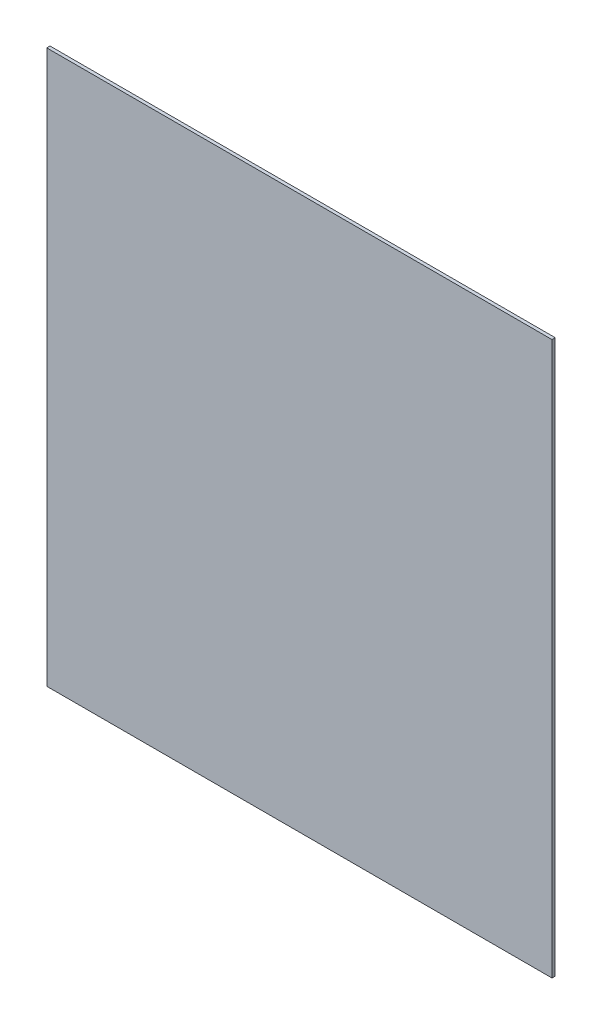
SolidWorks part; units mm, degrees
ref_plane "Přední rovina" through (0, 0, 0) normal (0, 0, 1) x (1, 0, 0)
ref_plane "Horní rovina" through (0, 0, 0) normal (0, 1, 0) x (1, 0, 0)
ref_plane "Pravá rovina" through (0, 0, 0) normal (1, 0, 0) x (0, 0, -1)
sketch "Skica1" plane through (0, 0, 0) normal (0, 0, 1) x (1, 0, 0)
  line L1 (-233, 255) -> (233, 255)
  line L2 (-233, 255) -> (-233, -255)
  line L3 (-233, -255) -> (233, -255)
  line L4 (233, 255) -> (233, -255)
  line L5 (-233, 255) -> (233, -255) construction
  line L6 (-233, -255) -> (233, 255) construction
  point P0 (0, 0)
  dimension "D1" = 466
  dimension "D2" = 510
extrude "Přidat vysunutím1" add sketch "Skica1" along normal blind 3
